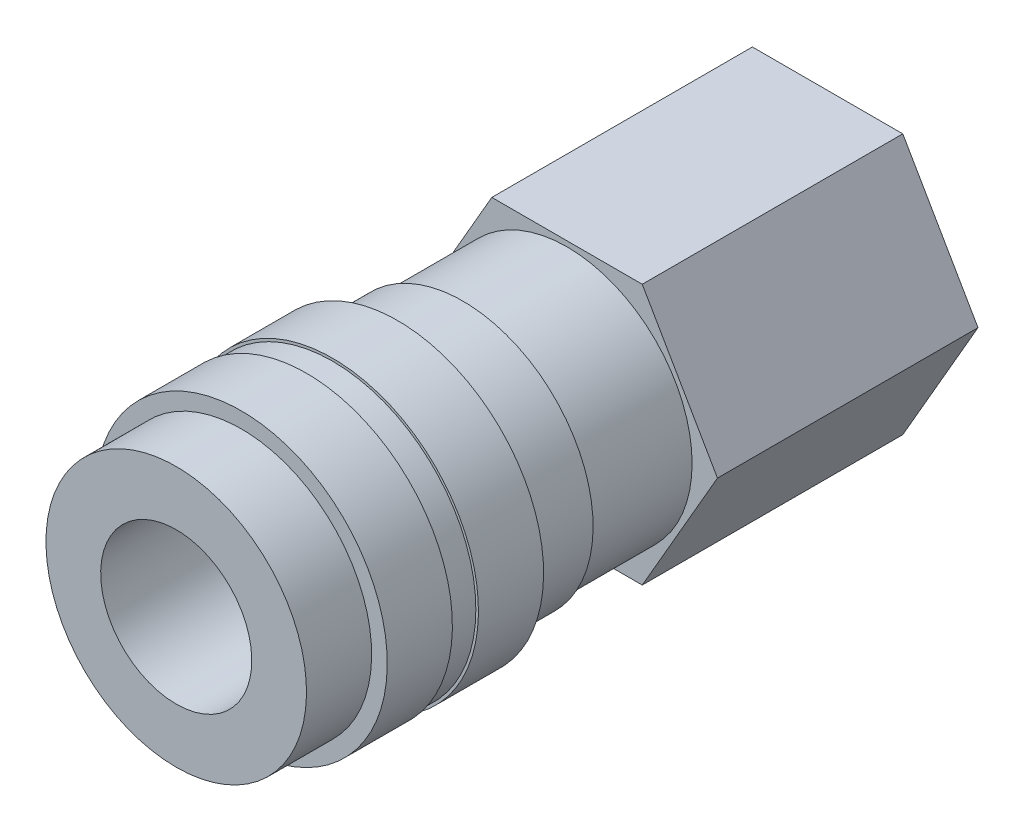
SolidWorks part; units mm, degrees
ref_plane "Front Plane" through (0, 0, 0) normal (0, 0, 1) x (1, 0, 0)
ref_plane "Top Plane" through (0, 0, 0) normal (0, 1, 0) x (1, 0, 0)
ref_plane "Right Plane" through (0, 0, 0) normal (1, 0, 0) x (0, 0, -1)
sketch "Sketch1" plane through (0, 0, 0) normal (1, 0, 0) x (0, 0, -1)
  line L0 (3.175, 6.35) -> (3.175, 7.112)
  line L1 (12.7, 0) -> (31.75, 0)
  line L2 (0, 3.683) -> (0, 6.35)
  line L3 (0, 6.35) -> (3.175, 6.35)
  line L4 (31.75, 0) -> (31.75, 17.5209)
  line L5 (3.175, 7.112) -> (6.35, 7.112)
  line L6 (6.35, 7.112) -> (6.35, 6.985)
  line L7 (6.35, 6.985) -> (7.62, 6.985)
  line L8 (7.62, 6.985) -> (7.62, 7.112)
  line L9 (7.62, 7.112) -> (10.795, 7.112)
  line L10 (10.795, 7.112) -> (10.795, 6.35)
  line L11 (10.795, 6.35) -> (13.97, 6.35)
  line L12 (13.97, 6.35) -> (13.97, 6.096)
  line L13 (13.97, 6.096) -> (19.05, 6.096)
  line L14 (19.05, 6.096) -> (19.05, 17.5209)
  line L15 (19.05, 17.5209) -> (31.75, 17.5209)
  line L16 (0, 3.683) -> (12.7, 3.683)
  line L17 (12.7, 3.683) -> (12.7, 0)
  dimension "D2" = 3.683
  dimension "D3" = 7.62
  dimension "D4" = 0.762
  dimension "D5" = 3.175
  dimension "D6" = 6.096
  dimension "D7" = 3.175
  dimension "D8" = 0.127
  dimension "D9" = 6.35
  dimension "D10" = 12.7
  dimension "D11" = 19.05
  dimension "D12" = 1.27
  dimension "D13" = 12.7
revolve "Revolve1" add sketch "Sketch1" angle 360 about L1
sketch "Sketch2" plane through (0, 0, -19.05) normal (0, 0, -1) x (-1, 0, 0)
  line L1 (7.3323, 0) -> (3.6662, 6.35)
  line L2 (3.6662, 6.35) -> (-3.6662, 6.35)
  line L3 (-3.6662, 6.35) -> (-7.3323, 0)
  line L4 (-7.3323, 0) -> (-3.6662, -6.35)
  line L5 (-3.6662, -6.35) -> (3.6662, -6.35)
  line L6 (3.6662, -6.35) -> (7.3323, 0)
  circle A0 centre (0, 0) radius 6.35 construction
  circle A1 centre (0, 0) radius 31.7328
  dimension "D1" = 12.7
extrude "Cut-Extrude1" cut sketch "Sketch2" along normal through all
hole_wizard "Pipe Tap Drill for 1/8 Tap1" positions "Sketch3" profile "Sketch4" hole size "1/8" standard "ANSI Inch"
sketch "Sketch3" plane through (0, 0, -31.75) normal (0, 0, -1) x (-1, 0, 0)
  point P0 (0, 0)
sketch "Sketch4" plane through (0, 0, -31.75) normal (1, 0, 0) x (0, 1, 0)
  line L0 (0, 0) -> (0, 8.8835)
  line L1 (0, 8.8835) -> (4.2164, 6.35)
  line L2 (4.2164, 6.35) -> (4.2164, 0)
  line L5 (4.2164, 0) -> (0, 0)
  line L10 (0, 8.8835) -> (-4.2164, 6.35) construction
  line L11 (0, -6.35) -> (0, 107.95) construction
  dimension "Hole Dia." = 8.4328
  dimension "Hole Depth" = 6.35
  dimension "Drill Angle" = 118
